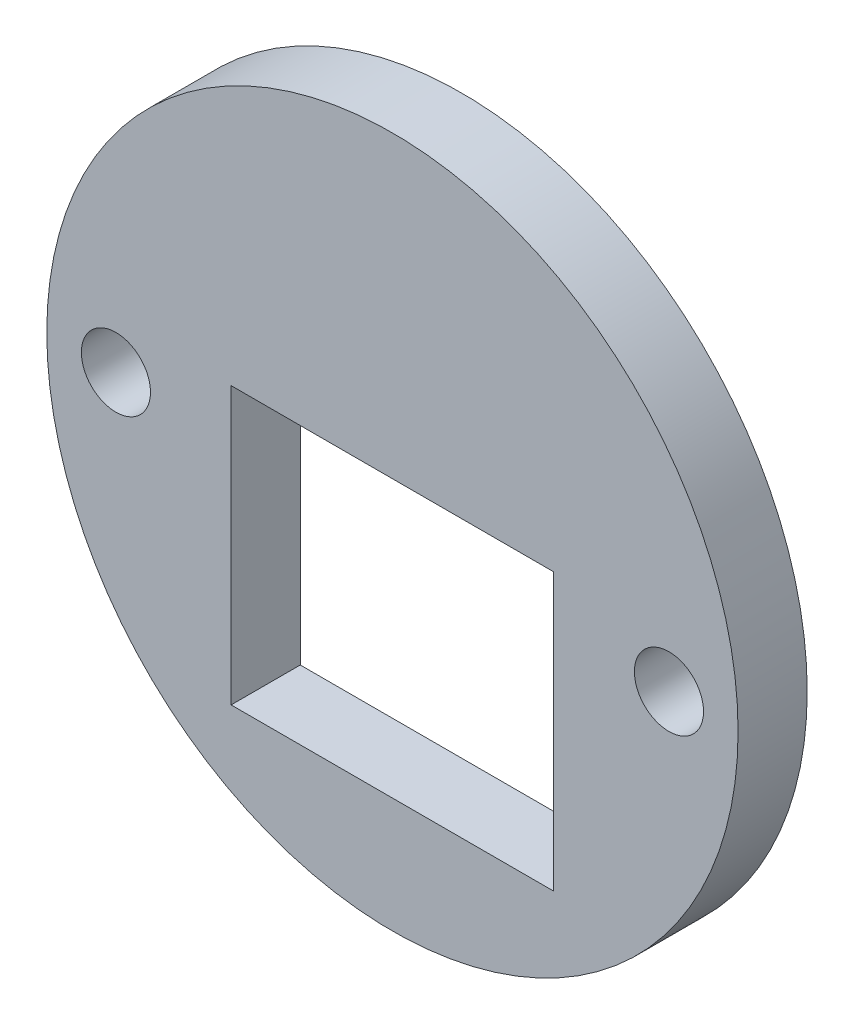
SolidWorks part; units mm, degrees
ref_plane "Front Plane" through (0, 0, 0) normal (0, 0, 1) x (1, 0, 0)
ref_plane "Top Plane" through (0, 0, 0) normal (0, 1, 0) x (1, 0, 0)
ref_plane "Right Plane" through (0, 0, 0) normal (1, 0, 0) x (0, 0, -1)
sketch "Sketch1" plane through (0, 0, 0) normal (0, 0, 1) x (1, 0, 0)
  line L1 (-7, 2) -> (7, 2)
  line L2 (-7, 2) -> (-7, -10)
  line L3 (-7, -10) -> (7, -10)
  line L4 (7, 2) -> (7, -10)
  circle A0 centre (0, 0) radius 15
  circle A1 centre (-12, 0) radius 1.5
  circle A2 centre (12, 0) radius 1.5
  dimension "D1" = 30
  dimension "D2" = 3
  dimension "D7" = 5
  dimension "D6" = 2
  dimension "D3" = 24
  dimension "D4" = 14
  dimension "D5" = 12
  dimension "D8" = 7
extrude "Boss-Extrude1" add sketch "Sketch1" along normal blind 3
